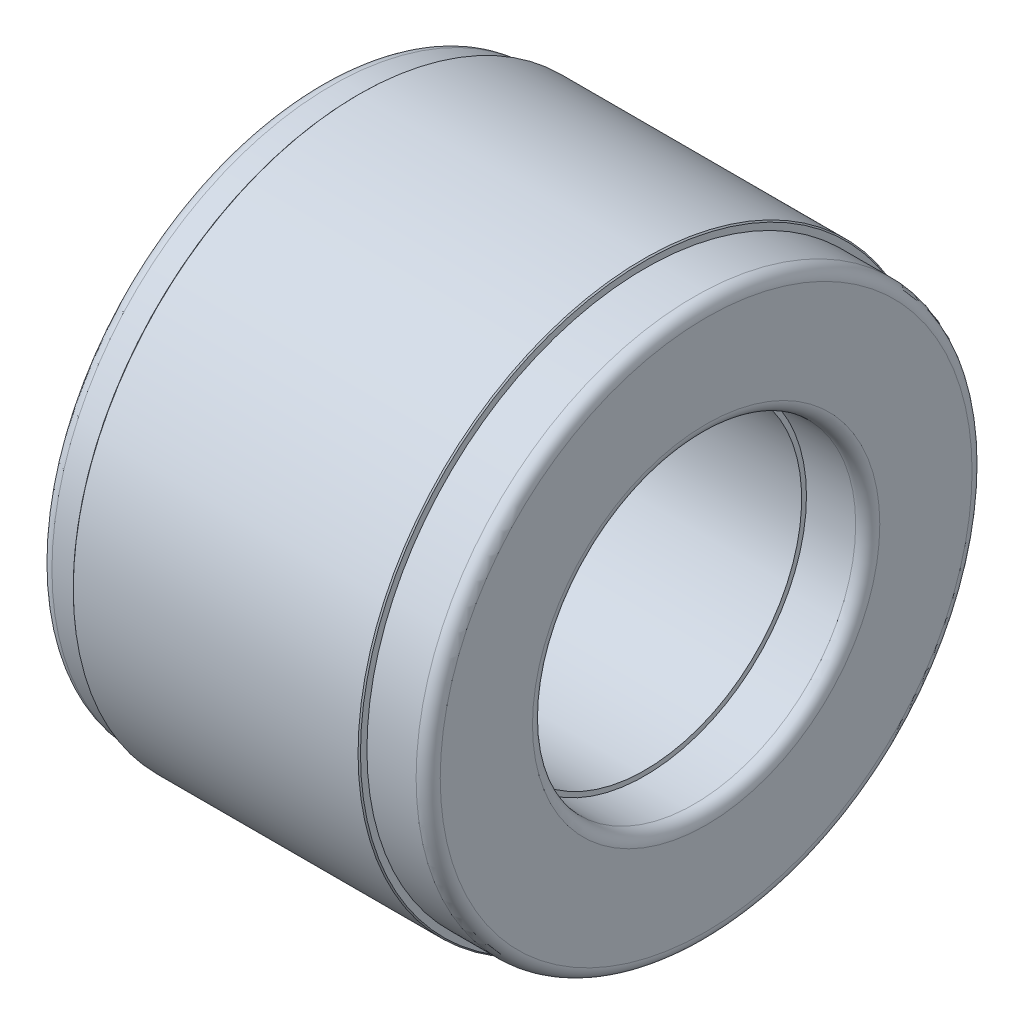
SolidWorks part; units mm, degrees
ref_plane "Front Plane" through (0, 0, 0) normal (0, 0, 1) x (1, 0, 0)
ref_plane "Top Plane" through (0, 0, 0) normal (0, 1, 0) x (1, 0, 0)
ref_plane "Right Plane" through (0, 0, 0) normal (1, 0, 0) x (0, 0, -1)
sketch "Sketch1" plane through (0, 0, 0) normal (0, 0, 1) x (1, 0, 0)
  line L0 (0, 0) -> (67.0891, 0) construction
  line L1 (0, 46.355) -> (0, 27.305)
  line L2 (0, 27.305) -> (6.35, 27.305)
  line L3 (6.35, 27.305) -> (6.35, 26)
  line L4 (6.35, 26) -> (53.98, 26)
  line L5 (53.98, 26) -> (53.98, 26.8)
  line L6 (53.98, 26.8) -> (64.14, 26.8)
  line L7 (64.14, 26.8) -> (64.14, 46.1)
  line L8 (64.14, 46.1) -> (53.98, 46.1)
  line L9 (53.98, 46.1) -> (53.98, 47.37)
  line L10 (53.98, 47.37) -> (6.35, 47.37)
  line L11 (6.35, 47.37) -> (6.35, 46.355)
  line L12 (6.35, 46.355) -> (0, 46.355)
  point P14 (6.35, 46.8625)
  dimension "D1" = 6.35
  dimension "D2" = 47.63
  dimension "D3" = 54.61
  dimension "D4" = 94.74
  dimension "D5" = 92.2
  dimension "D6" = 52
  dimension "D7" = 10.16
  dimension "D8" = 26.8
  dimension "D9" = 92.71
revolve "Revolve1" add sketch "Sketch1" angle 360 about L0
fillet "Fillet1" radius 2 4 edges at (0, 0, 27.305) (0, 0, 46.355) (64.14, 0, 26.8) (64.14, 0, 46.1)
chamfer "Chamfer1" distance 0.2 angle 45 2 edges at (53.98, 0, 47.37) (6.35, 0, 47.37)
